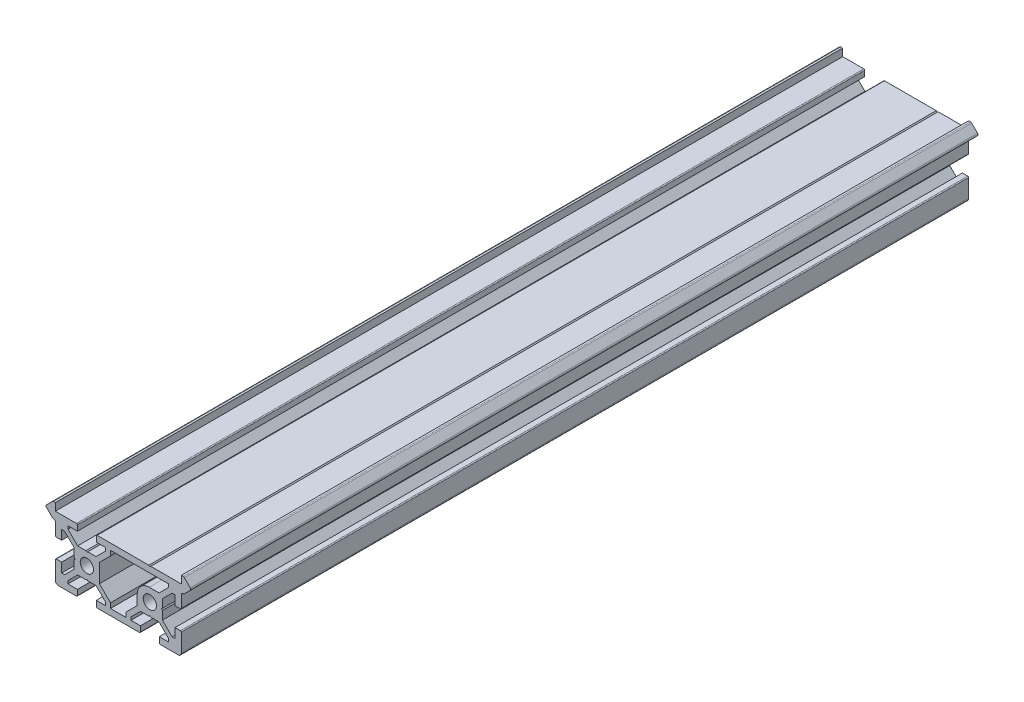
SolidWorks part; units mm, degrees
ref_plane "Front Plane" through (0, 0, 0) normal (0, 0, 1) x (1, 0, 0)
ref_plane "Top Plane" through (0, 0, 0) normal (0, 1, 0) x (1, 0, 0)
ref_plane "Right Plane" through (0, 0, 0) normal (1, 0, 0) x (0, 0, -1)
sketch "Model" plane through (0, 0, 0) normal (0, 0, 1) x (1, 0, 0)
  line L0 (0, 0) -> (0, 76.2) construction
  line L1 (0, 0) -> (101.6, 0) construction
  line L2 (0, 76.2) -> (101.6, 76.2) construction
  line L3 (101.6, 0) -> (101.6, 76.2) construction
  line L4 (28.7715, 48.1056) -> (30.6465, 49.9806)
  line L5 (31.5929, 50.127) -> (31.5929, 47.752)
  line L6 (31.5929, 44.877) -> (31.5929, 41.052)
  line L7 (31.5929, 34.452) -> (31.5929, 28.752)
  line L8 (33.5929, 31.752) -> (33.5929, 34.752)
  line L9 (33.5929, 40.752) -> (33.5929, 43.752)
  line L10 (35.5929, 29.752) -> (35.5929, 30.6914)
  line L11 (35.5929, 44.8127) -> (35.5929, 45.752)
  line L12 (37.5929, 40.6914) -> (37.5929, 38.052)
  line L13 (37.5929, 37.452) -> (37.5929, 34.8127)
  line L14 (38.5929, 28.052) -> (38.5929, 29.752)
  line L15 (38.5929, 45.752) -> (38.5929, 47.452)
  line L16 (32.5929, 27.752) -> (38.2929, 27.752)
  line L17 (44.8929, 27.752) -> (58.2929, 27.752)
  line L18 (64.8929, 27.752) -> (70.5929, 27.752)
  line L19 (37.5929, 38.052) -> (37.8929, 37.752)
  line L20 (41.5929, 34.052) -> (41.8929, 33.752)
  line L21 (30.6465, 45.5235) -> (28.7715, 47.3985)
  line L22 (41.8929, 41.752) -> (41.5929, 41.452)
  line L23 (37.8929, 37.752) -> (37.5929, 37.452)
  line L24 (67.5929, 29.752) -> (64.5929, 29.752)
  line L25 (58.5929, 29.752) -> (55.5929, 29.752)
  line L26 (54.0929, 29.752) -> (49.0929, 29.752)
  line L27 (47.5929, 29.752) -> (44.5929, 29.752)
  line L28 (38.5929, 29.752) -> (35.5929, 29.752)
  line L29 (34.5323, 43.752) -> (37.5929, 40.6914)
  line L30 (44.5323, 33.752) -> (47.5929, 30.6914)
  line L31 (44.5929, 47.452) -> (44.5929, 45.752)
  line L32 (44.5929, 29.752) -> (44.5929, 28.052)
  line L33 (47.5929, 44.8127) -> (44.5323, 41.752)
  line L34 (37.5929, 34.8127) -> (34.5323, 31.752)
  line L35 (69.5929, 31.752) -> (68.6536, 31.752)
  line L36 (34.5323, 31.752) -> (33.5929, 31.752)
  line L37 (49.0929, 31.3127) -> (45.5929, 34.8127)
  line L38 (38.6536, 41.752) -> (35.5929, 44.8127)
  line L39 (45.5929, 34.8127) -> (45.5929, 40.6914)
  line L40 (35.5929, 30.6914) -> (38.6536, 33.752)
  line L41 (45.5929, 40.6914) -> (49.0929, 44.1914)
  line L42 (38.6536, 33.752) -> (41.2929, 33.752)
  line L43 (41.8929, 33.752) -> (44.5323, 33.752)
  line L44 (58.6536, 33.752) -> (61.2929, 33.752)
  line L45 (61.8929, 33.752) -> (64.5323, 33.752)
  line L46 (41.5929, 41.452) -> (41.2929, 41.752)
  line L47 (47.5929, 45.752) -> (47.5929, 44.8127)
  line L48 (47.5929, 30.6914) -> (47.5929, 29.752)
  line L49 (41.2929, 33.752) -> (41.5929, 34.052)
  line L50 (71.2929, 34.752) -> (69.5929, 34.752)
  line L51 (33.5929, 34.752) -> (31.8929, 34.752)
  line L52 (49.0929, 29.752) -> (49.0929, 31.3127)
  line L53 (49.0929, 44.1914) -> (49.0929, 45.752)
  line L54 (61.5929, 47.452) -> (61.8929, 47.752)
  line L55 (31.8929, 40.752) -> (33.5929, 40.752)
  line L56 (69.5929, 40.752) -> (71.2929, 40.752)
  line L57 (54.0929, 31.3127) -> (54.0929, 29.752)
  line L58 (64.5323, 41.752) -> (61.4029, 41.752)
  line L59 (44.5323, 41.752) -> (41.8929, 41.752)
  line L60 (41.2929, 41.752) -> (38.6536, 41.752)
  line L61 (61.5929, 34.052) -> (61.8929, 33.752)
  line L62 (55.5929, 29.752) -> (55.5929, 30.6914)
  line L63 (33.5929, 43.752) -> (34.5323, 43.752)
  line L64 (68.6536, 43.752) -> (69.5929, 43.752)
  line L65 (57.5929, 37.942) -> (57.5929, 34.8127)
  line L66 (58.5929, 28.052) -> (58.5929, 29.752)
  line L67 (31.0929, 45.377) -> (31, 45.377)
  line L68 (72.0929, 45.377) -> (72.1858, 45.377)
  line L69 (35.5929, 45.752) -> (38.5929, 45.752)
  line L70 (44.5929, 45.752) -> (47.5929, 45.752)
  line L71 (49.0929, 45.752) -> (67.5929, 45.752)
  line L72 (64.5323, 33.752) -> (67.5929, 30.6914)
  line L73 (68.6536, 31.752) -> (65.5929, 34.8127)
  line L74 (67.5929, 44.8127) -> (64.5323, 41.752)
  line L75 (57.5929, 34.8127) -> (54.0929, 31.3127)
  line L76 (55.5929, 30.6914) -> (58.6536, 33.752)
  line L77 (65.5929, 40.6914) -> (68.6536, 43.752)
  line L78 (72.5394, 45.5235) -> (74.4144, 47.3985)
  line L79 (71.5929, 47.752) -> (61.8929, 47.752)
  line L80 (61.2929, 47.752) -> (44.8929, 47.752)
  line L81 (38.2929, 47.752) -> (31.5929, 47.752)
  line L82 (65.5929, 37.452) -> (65.2929, 37.752)
  line L83 (61.2929, 33.752) -> (61.5929, 34.052)
  line L84 (65.2929, 37.752) -> (65.5929, 38.052)
  line L85 (72.1858, 50.127) -> (71.5929, 50.127)
  line L86 (31, 50.127) -> (31.5929, 50.127)
  line L87 (64.5929, 29.752) -> (64.5929, 28.052)
  line L88 (61.2929, 47.752) -> (61.5929, 47.452)
  line L89 (65.5929, 34.8127) -> (65.5929, 37.452)
  line L90 (65.5929, 38.052) -> (65.5929, 40.6914)
  line L91 (67.5929, 45.752) -> (67.5929, 44.8127)
  line L92 (67.5929, 30.6914) -> (67.5929, 29.752)
  line L93 (69.5929, 43.752) -> (69.5929, 40.752)
  line L94 (69.5929, 34.752) -> (69.5929, 31.752)
  line L95 (71.5929, 50.127) -> (71.5929, 47.752)
  line L96 (71.5929, 28.752) -> (71.5929, 34.452)
  line L97 (71.5929, 41.052) -> (71.5929, 44.877)
  line L98 (74.4144, 48.1056) -> (72.5394, 49.9806)
  arc A0 (61.4029, 41.752) -> (57.5929, 37.942) centre (61.4029, 37.942) ccw
  circle A1 centre (61.5929, 37.752) radius 2.1
  circle A2 centre (41.5929, 37.752) radius 2.1
  arc A3 (31.5929, 28.752) -> (32.5929, 27.752) centre (32.5929, 28.752) ccw
  arc A4 (70.5929, 27.752) -> (71.5929, 28.752) centre (70.5929, 28.752) ccw
  arc A5 (31.5929, 44.877) -> (31.0929, 45.377) centre (31.0929, 44.877) ccw
  arc A6 (72.0929, 45.377) -> (71.5929, 44.877) centre (72.0929, 44.877) ccw
  arc A7 (31, 50.127) -> (30.6465, 49.9806) centre (31, 49.627) ccw
  arc A8 (28.7715, 48.1056) -> (28.7715, 47.3985) centre (29.125, 47.752) ccw
  arc A9 (30.6465, 45.5235) -> (31, 45.377) centre (31, 45.877) ccw
  arc A10 (72.5394, 49.9806) -> (72.1858, 50.127) centre (72.1858, 49.627) ccw
  arc A11 (74.4144, 47.3985) -> (74.4144, 48.1056) centre (74.0608, 47.752) ccw
  arc A12 (72.1858, 45.377) -> (72.5394, 45.5235) centre (72.1858, 45.877) ccw
  arc A13 (31.8929, 34.752) -> (31.5929, 34.452) centre (31.8929, 34.452) ccw
  arc A14 (44.8929, 47.752) -> (44.5929, 47.452) centre (44.8929, 47.452) ccw
  arc A15 (38.5929, 47.452) -> (38.2929, 47.752) centre (38.2929, 47.452) ccw
  arc A16 (31.5929, 41.052) -> (31.8929, 40.752) centre (31.8929, 41.052) ccw
  arc A17 (38.2929, 27.752) -> (38.5929, 28.052) centre (38.2929, 28.052) ccw
  arc A18 (44.5929, 28.052) -> (44.8929, 27.752) centre (44.8929, 28.052) ccw
  arc A19 (58.2929, 27.752) -> (58.5929, 28.052) centre (58.2929, 28.052) ccw
  arc A20 (64.5929, 28.052) -> (64.8929, 27.752) centre (64.8929, 28.052) ccw
  arc A21 (71.5929, 34.452) -> (71.2929, 34.752) centre (71.2929, 34.452) ccw
  arc A22 (71.2929, 40.752) -> (71.5929, 41.052) centre (71.2929, 41.052) ccw
extrude "Boss-Extrude1" add sketch "Model" along normal blind 250
ref_plane "Plane1" through (51.5929, 0, 0) normal (-1, 0, 0) x (0, 0, 1)
